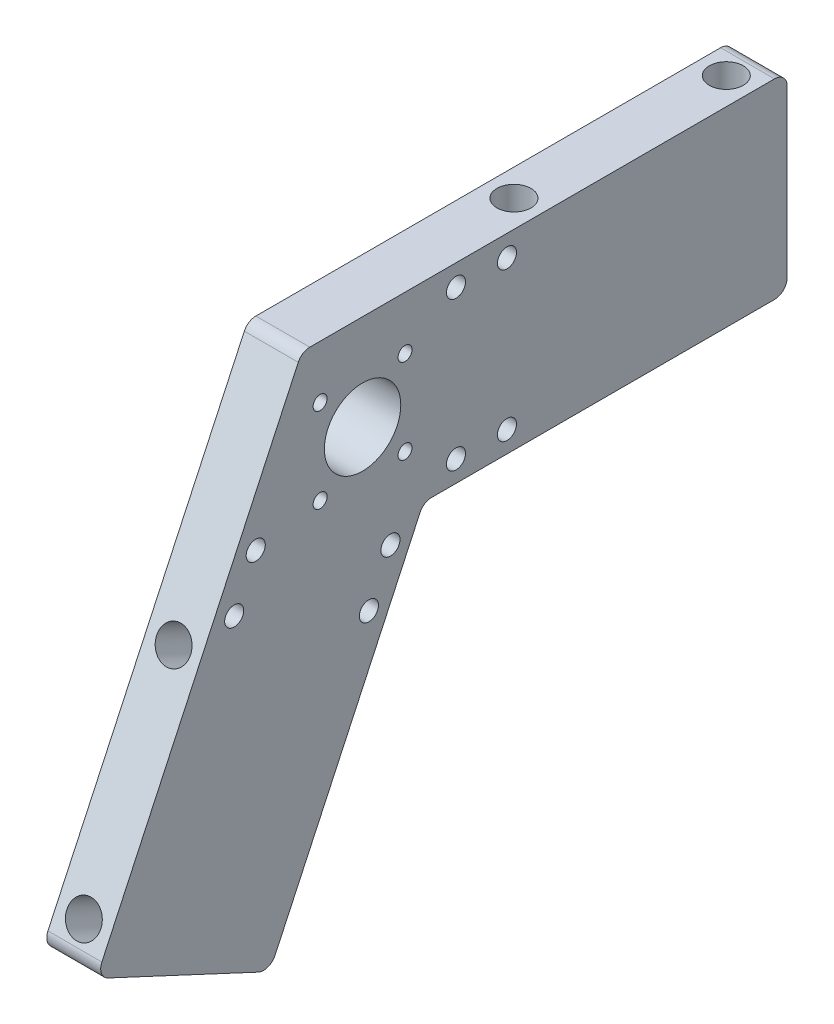
SolidWorks part; units mm, degrees
ref_plane "Alzado" through (0, 0, 0) normal (0, 0, 1) x (1, 0, 0)
ref_plane "Planta" through (0, 0, 0) normal (0, 1, 0) x (1, 0, 0)
ref_plane "Vista lateral" through (0, 0, 0) normal (1, 0, 0) x (0, 0, -1)
sketch "Croquis1" plane through (0, 0, 0) normal (1, 0, 0) x (0, 0, -1)
  line L0 (0, 0) -> (100, 0) construction
  line L1 (0, 0) -> (-42.2618, -90.6308) construction
  line L2 (14.3341, -22.5) -> (-21.8699, -100.1397)
  line L3 (14.3341, -22.5) -> (100, -22.5)
  line L4 (-14.3341, 22.5) -> (-62.6538, -81.1219)
  line L5 (-14.3341, 22.5) -> (100, 22.5)
  line L6 (100, 22.5) -> (100, -22.5)
  line L7 (0, 0) -> (100, 0) construction
  line L8 (-62.6538, -81.1219) -> (-21.8699, -100.1397)
  circle A0 centre (0, 0) radius 9
  point P11 (100, 0)
  dimension "D1" = 18
  dimension "D2" = 115
  dimension "D3" = 45
  dimension "D4" = 100
  dimension "50" = 100
extrude "Saliente-Extruir1" add sketch "Croquis1" along normal mid plane 12.7
hole_wizard "Diámetro de taladro Ø5.0 (5)1" positions "Croquis2" profile "Croquis3" hole size "Ø5.0" standard "Ansi Metric" end condition up to next
sketch "Croquis2" plane through (0, 22.5, 0) normal (0, 1, 0) x (1, 0, 0)
  line L0 (6.35, 100) -> (-6.35, 100) construction
  point P0 (0, 92)
  point P2 (0, 42)
  dimension "D1" = 50
  dimension "D2" = 8
sketch "Croquis3" plane through (0, 22.5, -92) normal (1, 0, 0) x (0, 0, 1)
  line L0 (0, 0) -> (0, 45)
  line L1 (0, 45) -> (4, 45)
  line L2 (4, 45) -> (4, 0)
  line L5 (4, 0) -> (0, 0)
  line L11 (0, -6.35) -> (0, 107.95) construction
  dimension "Diámetro de taladro hasta el siguiente" = 8
  dimension "Profundidad de taladro hasta el siguiente" = 45
hole_wizard "Diámetro de taladro Ø5.0 (5)2" positions "Croquis4" profile "Croquis5" hole size "Ø5.0" standard "Ansi Metric" end condition up to next
sketch "Croquis4" plane through (0, 9.5089, 20.3919) normal (0, 0.4226, 0.9063) x (1, 0, 0)
  line L0 (6.35, -100) -> (-6.35, -100) construction
  point P0 (0, -42)
  point P2 (0, -92)
  dimension "D1" = 50
  dimension "D2" = 8
sketch "Croquis5" plane through (0, -28.556, 38.1419) normal (1, 0, 0) x (0, -0.9063, 0.4226)
  line L0 (0, 0) -> (0, 45)
  line L1 (0, 45) -> (4, 45)
  line L2 (4, 45) -> (4, 0)
  line L5 (4, 0) -> (0, 0)
  line L11 (0, -6.35) -> (0, 107.95) construction
  dimension "Diámetro de taladro hasta el siguiente" = 8
  dimension "Profundidad de taladro hasta el siguiente" = 45
fillet "Redondeo1" radius 3 6 edges at (0, 22.5, -100) (0, -22.5, -100) (0, -100.1397, 21.8699) (0, -81.1219, 62.6538) (0, 22.5, 14.3341) (0, -22.5, -14.3341)
hole_wizard "Taladro roscado M4x0.71" positions "Croquis6" profile "Croquis7" tap size "M4x0.7" standard "Ansi Metric" end condition up to next
sketch "Croquis6" plane through (-6.35, 0, 0) normal (-1, 0, 0) x (0, 0, 1)
  point P0 (10, 10)
  point P3 (-10, 10)
  point P6 (-10, -10)
  point P9 (10, -10)
sketch "Croquis7" plane through (-6.35, 10, 10) normal (0, 1, 0) x (0, 0, 1)
  line L0 (0, 0) -> (0, 12.7)
  line L1 (0, 12.7) -> (1.65, 12.7)
  line L2 (1.65, 12.7) -> (1.65, 0)
  line L5 (1.65, 0) -> (0, 0)
  line L11 (0, -6.35) -> (0, 107.95) construction
  dimension "Diámetro de perforador para roscar hasta el siguiente" = 3.3
  dimension "Profundidad de perforador para roscar hasta el siguiente" = 12.7
cosmetic thread "Rosca de taladro1" parameters "D2"=4
cosmetic thread "Rosca de taladro2" parameters "D2"=4
cosmetic thread "Rosca de taladro3" parameters "D2"=4
cosmetic thread "Rosca de taladro4" parameters "D2"=4
hole_wizard "Taladro de margen para M41" positions "Croquis8" profile "Croquis9" hole size "M4" standard "Ansi Metric" end condition up to next
sketch "Croquis8" plane through (-6.35, 0, 0) normal (-1, 0, 0) x (0, 0, 1)
  line L0 (-6.5628, -27.3346) -> (-1.4914, -38.2103) construction
  line L1 (-1.4914, -38.2103) -> (30.2294, -23.4186) construction
  line L2 (30.2294, -23.4186) -> (25.158, -12.543) construction
  line L3 (25.158, -12.543) -> (-6.5628, -27.3346) construction
  line L5 (0, 0) -> (9.2976, -19.9388) construction
  line L7 (15.1418, 20.7679) -> (61.3859, -78.4029) construction
  line L8 (-22, 17.5) -> (-22, -17.5) construction
  line L9 (-22, -17.5) -> (-34, -17.5) construction
  line L10 (-34, -17.5) -> (-34, 17.5) construction
  line L11 (-34, 17.5) -> (-22, 17.5) construction
  line L13 (0, 0) -> (-22, 0) construction
  point P0 (-6.5628, -27.3346)
  point P2 (-1.4914, -38.2103)
  point P4 (25.158, -12.543)
  point P6 (30.2294, -23.4186)
  point P24 (-22, 17.5)
  point P26 (-22, -17.5)
  point P28 (-34, 17.5)
  point P30 (-34, -17.5)
  dimension "D1" = 12
  dimension "D2" = 22
  dimension "D3" = 35
  dimension "D4" = 22
  dimension "D5" = 35
  dimension "D6" = 12
sketch "Croquis9" plane through (-6.35, -27.3346, -6.5628) normal (0, 1, 0) x (0, 0, 1)
  line L0 (0, 0) -> (0, 12.7)
  line L1 (0, 12.7) -> (2.25, 12.7)
  line L2 (2.25, 12.7) -> (2.25, 0)
  line L5 (2.25, 0) -> (0, 0)
  line L11 (0, -6.35) -> (0, 107.95) construction
  dimension "Diámetro de taladro hasta el siguiente" = 4.5
  dimension "Profundidad de taladro hasta el siguiente" = 12.7
